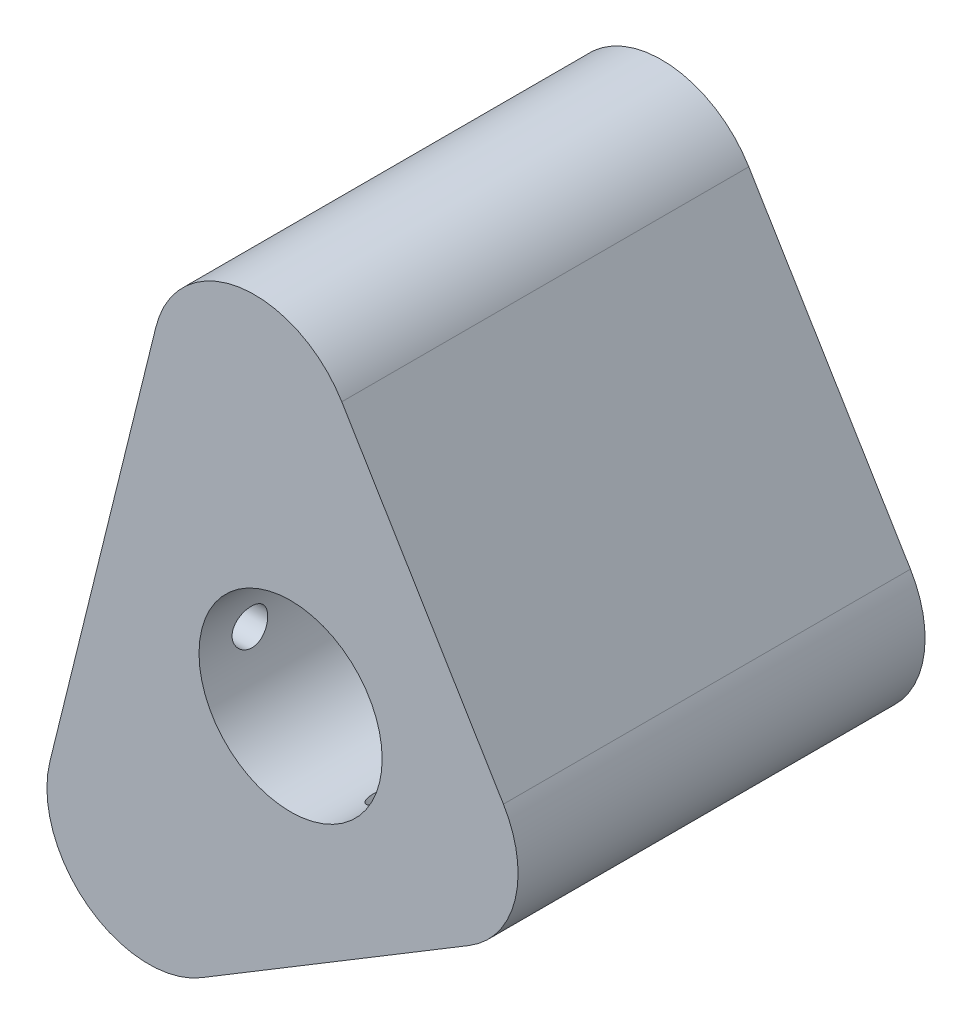
SolidWorks part; units mm, degrees
ref_plane "Front Plane" through (0, 0, 0) normal (0, 0, 1) x (1, 0, 0)
ref_plane "Top Plane" through (0, 0, 0) normal (0, 1, 0) x (1, 0, 0)
ref_plane "Right Plane" through (0, 0, 0) normal (1, 0, 0) x (0, 0, -1)
sketch "Sketch1" plane through (0, 0, 0) normal (0, 0, 1) x (1, 0, 0)
  line L0 (-13.9462, -18.9369) -> (-3.5289, 23.2519) construction
  line L1 (-3.5289, 23.2519) -> (12.3568, -3.0512) construction
  line L2 (12.3568, -3.0512) -> (-13.9462, -18.9369) construction
  line L3 (-23.6546, -16.5397) -> (-13.2373, 25.6491)
  line L4 (5.031, 28.4217) -> (20.9168, 2.1186)
  line L5 (17.5266, -11.6111) -> (-8.7764, -27.4969)
  line L6 (26.0866, -6.4413) -> (-29.442, -39.9779) construction
  line L7 (-29.442, -39.9779) -> (-7.45, 49.0873) construction
  line L8 (-7.45, 49.0873) -> (26.0866, -6.4413) construction
  circle A0 centre (0, 0) radius 9
  arc A3 (-23.6546, -16.5397) -> (-8.7764, -27.4969) centre (-13.9462, -18.9369) ccw
  arc A4 (5.031, 28.4217) -> (-13.2373, 25.6491) centre (-3.5289, 23.2519) ccw
  arc A5 (17.5266, -11.6111) -> (20.9168, 2.1186) centre (12.3568, -3.0512) ccw
  dimension "D1" = 18
  dimension "D2" = 45
  dimension "D3" = 45
  dimension "D4" = 10
extrude "Boss-Extrude1" add sketch "Sketch1" along normal blind 70
sketch "Sketch2" plane through (9.8226, -16.2639, 0) normal (0.517, -0.856, 0) x (0.856, 0.517, 0)
  line L0 (-21.7279, 70) -> (9, 70) construction
  circle A0 centre (0, 65) radius 2.5
  dimension "D1" = 5
  dimension "D2" = 5
extrude "Cut-Extrude1" cut sketch "Sketch2" against normal blind 5
sketch "Sketch3" plane through (7.2377, -11.984, 0) normal (0.517, -0.856, 0) x (0.856, 0.517, 0)
  circle A0 centre (0, 65) radius 1.75
  dimension "D1" = 3.5
extrude "Cut-Extrude2" cut sketch "Sketch3" against normal up to surface (5.1718 mm away)
pattern_circular "CirPattern1" count 3 over 360 about axis through (0, 0, 0) along (0, 0, 1) of "Cut-Extrude1", "Cut-Extrude2"
sketch "Sketch5" plane through (0, 0, 0) normal (0, 1, 0) x (1, 0, 0)
  line L0 (-24.5682, 0) -> (0, 0) construction
  line L2 (-24.5682, -30) -> (0, -30)
  line L3 (-24.5682, -5) -> (0, -5)
  line L4 (0, 0) -> (0, -30) construction
  line L6 (-24.5682, -30) -> (-24.5682, -5)
  line L7 (0, -30) -> (0, -5)
  dimension "D1" = 5
  dimension "D2" = 25
revolve "Cut-Revolve1" cut sketch "Sketch5" angle 360 about L4
sketch "Sketch6" plane through (0, 0, 0) normal (0, 0, -1) x (-1, 0, 0)
  circle A0 centre (0, 0) radius 9
extrude "Boss-Extrude2" add sketch "Sketch6" against normal up to surface (5 mm away) up to face at (9, 0, 5)
sketch "Sketch8" plane through (0, 0, 30) normal (0, 0, -1) x (-1, 0, 0)
  circle A0 centre (0, 0) radius 9 construction
  circle A1 centre (0, 0) radius 9
extrude "Boss-Extrude3" add sketch "Sketch8" against normal blind 3
sketch "Sketch9" plane through (0, 0, 0) normal (0, 0, -1) x (-1, 0, 0)
  circle A0 centre (0, 0) radius 8 construction
  circle A1 centre (0, 8) radius 1.875
  circle A2 centre (8, 0) radius 1.875
  circle A3 centre (0, -8) radius 1.875
  circle A4 centre (-8, 0) radius 1.875
  point P14 (0, 0)
  dimension "D1" = 16
  dimension "D2" = 3.75
  dimension "D3" = 4
extrude "Cut-Extrude3" cut sketch "Sketch9" against normal up to surface (5 mm away)
sketch "Sketch10" plane through (0, 0, 30) normal (0, 0, -1) x (-1, 0, 0)
  line L1 (13.2373, 25.6491) -> (23.6546, -16.5397) construction
  line L2 (8.7764, -27.4969) -> (-17.5266, -11.6111) construction
  line L3 (-20.9168, 2.1186) -> (-5.031, 28.4217) construction
  line L4 (13.2373, 25.6491) -> (23.6546, -16.5397)
  line L5 (8.7764, -27.4969) -> (-17.5266, -11.6111)
  line L6 (-20.9168, 2.1186) -> (-5.031, 28.4217)
  arc A0 (13.2373, 25.6491) -> (-5.031, 28.4217) centre (3.5289, 23.2519) ccw construction
  arc A1 (8.7764, -27.4969) -> (23.6546, -16.5397) centre (13.9462, -18.9369) ccw construction
  arc A2 (-20.9168, 2.1186) -> (-17.5266, -11.6111) centre (-12.3568, -3.0512) ccw construction
  arc A3 (13.2373, 25.6491) -> (-5.031, 28.4217) centre (3.5289, 23.2519) ccw
  arc A4 (8.7764, -27.4969) -> (23.6546, -16.5397) centre (13.9462, -18.9369) ccw
  arc A5 (-20.9168, 2.1186) -> (-17.5266, -11.6111) centre (-12.3568, -3.0512) ccw
sketch "Sketch11" plane through (0, 0, 0) normal (0, 0, -1) x (-1, 0, 0)
  circle A0 centre (0, 0) radius 4
  dimension "D1" = 8
extrude "Cut-Extrude4" cut sketch "Sketch11" against normal blind 3
sketch "Sketch12" plane through (0, 0, 0) normal (0, 1, 0) x (1, 0, 0)
  line L0 (-30.7423, -30) -> (34.4283, -30)
  line L1 (34.4283, -30) -> (34.4283, 3.2197)
  line L2 (34.4283, 3.2197) -> (-30.7423, 3.2197)
  line L3 (-30.7423, 3.2197) -> (-30.7423, -30)
extrude "Cut-Extrude5" cut sketch "Sketch12" against normal through all and the other way through all
sketch "Sketch13" plane through (-18.446, 4.5547, 0) normal (-0.9708, 0.2397, 0) x (0, 0, 1)
  line L4 (25.1827, 0) -> (50.8173, 0) construction
  line L8 (30, 21.7279) -> (30, -21.7279) construction
  circle A0 centre (38, 0) radius 5
  point P6 (30, 0)
  dimension "D1" = 10
  dimension "D2" = 8
extrude "Cut-Extrude6" cut sketch "Sketch13" against normal up to next
equation "\"fuse_diam\"= 0.07"
equation "\"fuse_rad\"= 0.035"
equation "\"battery_length\"= 0.076"
equation "\"battery_width\"= 0.034"
equation "\"battery_height\"= 0.051"
equation "\"bat_bay_length\"= 0.096"
equation "\"wing_shelf\"= 0.0175"
equation "\"shell\"= 0.002"
equation "\"chord_length\"= 0.089"
equation "\"tail_length\"= 0.26532000000000006"
equation "\"tail_diam\"= 0.035"
equation "\"connector\"= 0.06633000000000001"
